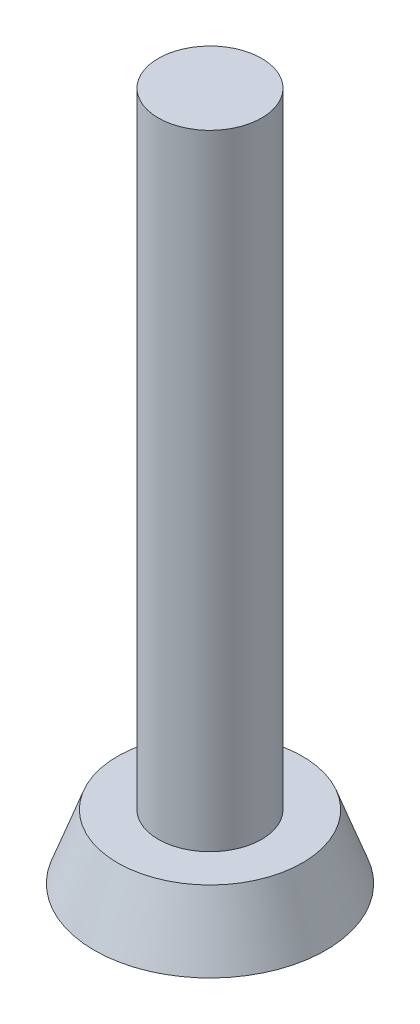
SolidWorks part; units mm, degrees
ref_plane "Front Plane" through (0, 0, 0) normal (0, 0, 1) x (1, 0, 0)
ref_plane "Top Plane" through (0, 0, 0) normal (0, 1, 0) x (1, 0, 0)
ref_plane "Right Plane" through (0, 0, 0) normal (1, 0, 0) x (0, 0, -1)
sketch "Sketch1" plane through (0, 0, 0) normal (0, 1, 0) x (1, 0, 0)
  circle A0 centre (0, 0) radius 3.36
  dimension "D1" = 6.72
extrude "Boss-Extrude1" add sketch "Sketch1" along normal blind 1.86 draft 20
sketch "Sketch2" plane through (0, 1.86, 0) normal (0, 1, 0) x (1, 0, 0)
  circle A0 centre (0, 0) radius 1.5
  dimension "D1" = 3
extrude "Boss-Extrude2" add sketch "Sketch2" along normal blind 18.14
sketch "Sketch3" plane through (0, 0, 0) normal (0, -1, 0) x (1, 0, 0)
  line L1 (0, 1.1547) -> (-1, 0.5774)
  line L2 (-1, 0.5774) -> (-1, -0.5774)
  line L3 (-1, -0.5774) -> (0, -1.1547)
  line L4 (0, -1.1547) -> (1, -0.5774)
  line L5 (1, -0.5774) -> (1, 0.5774)
  line L6 (1, 0.5774) -> (0, 1.1547)
  circle A0 centre (0, 0) radius 1 construction
  dimension "D1" = 2
extrude "Cut-Extrude1" cut sketch "Sketch3" against normal blind 1.5
